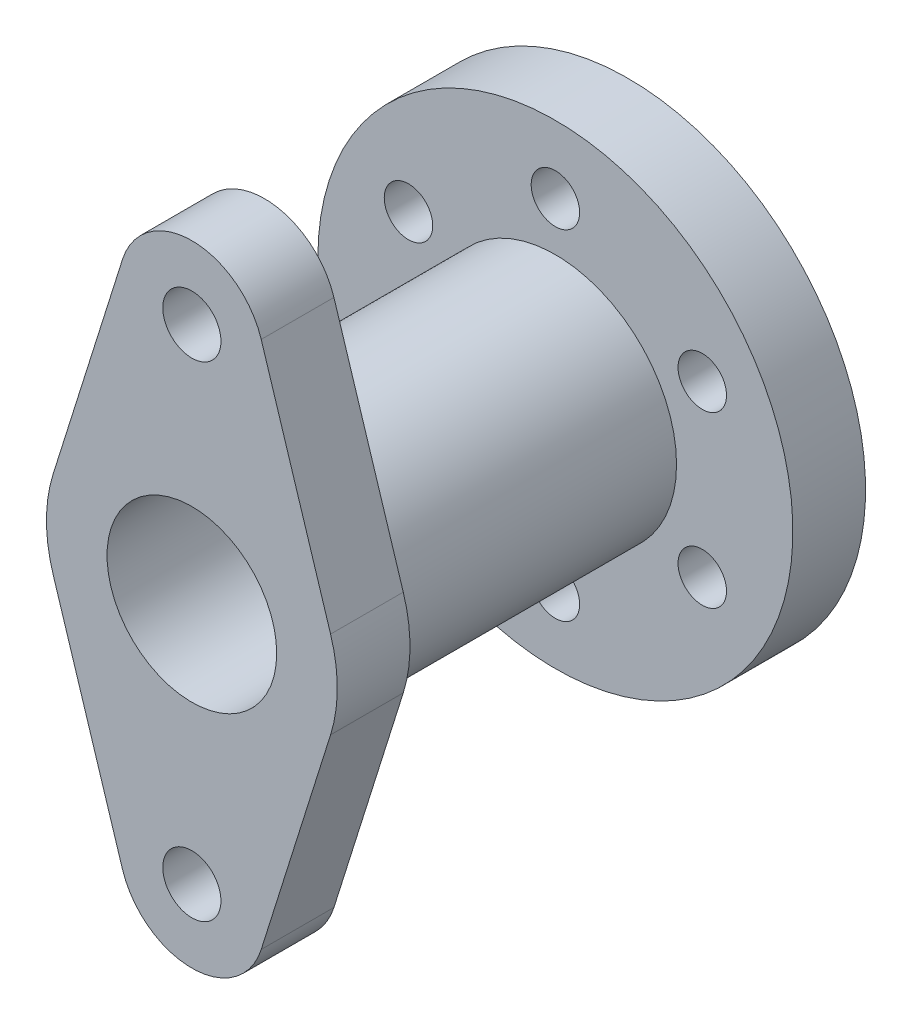
SolidWorks part; units mm, degrees
ref_plane "Front Plane" through (0, 0, 0) normal (0, 0, 1) x (1, 0, 0)
ref_plane "Top Plane" through (0, 0, 0) normal (0, 1, 0) x (1, 0, 0)
ref_plane "Right Plane" through (0, 0, 0) normal (1, 0, 0) x (0, 0, -1)
sketch "Sketch2" plane through (0, 0, 0) normal (0, 0, 1) x (1, 0, 0)
  line L1 (14.3091, 54.5) -> (28.6182, 9)
  line L2 (-14.3091, 54.5) -> (-28.6182, 9)
  line L4 (-14.3091, -54.5) -> (-28.6182, -9)
  line L5 (14.3091, -54.5) -> (28.6182, -9)
  arc A0 (-28.6182, 9) -> (-28.6182, -9) centre (0, 0) ccw
  arc A1 (14.3091, 54.5) -> (-14.3091, 54.5) centre (0, 50) ccw
  circle A2 centre (0, 50) radius 6
  circle A3 centre (0, 0) radius 17.5
  arc A4 (28.6182, -9) -> (28.6182, 9) centre (0, 0) ccw
  circle A5 centre (0, -50) radius 6
  arc A6 (14.3091, -54.5) -> (-14.3091, -54.5) centre (0, -50) cw
extrude "Boss-Extrude1" add sketch "Sketch2" along normal blind 15
sketch "Sketch3" plane through (0, 0, 0) normal (0, 0, -1) x (-1, 0, 0)
  circle A0 centre (0, 0) radius 25
  dimension "D1" = 50
extrude "Boss-Extrude3" add sketch "Sketch3" along normal blind 60
sketch "Sketch4" plane through (0, 0, -60) normal (0, 0, -1) x (-1, 0, 0)
  circle A0 centre (0, 0) radius 49
  dimension "D1" = 98
extrude "Boss-Extrude4" add sketch "Sketch4" along normal blind 15
sketch "Sketch5" plane through (0, 0, -75) normal (0, 0, -1) x (-1, 0, 0)
  circle A1 centre (0, 35) radius 5
  circle A2 centre (30.3109, 17.5) radius 5
  circle A3 centre (30.3109, -17.5) radius 5
  circle A4 centre (0, -35) radius 5
  circle A5 centre (-30.3109, -17.5) radius 5
  circle A6 centre (-30.3109, 17.5) radius 5
extrude "Cut-Extrude1" cut sketch "Sketch5" against normal blind 15
sketch "Sketch6" plane through (0, 0, 0) normal (0, 0, 1) x (1, 0, 0)
  circle A0 centre (0, 0) radius 17.5
  dimension "D1" = 35
extrude "Cut-Extrude2" cut sketch "Sketch6" against normal through all
